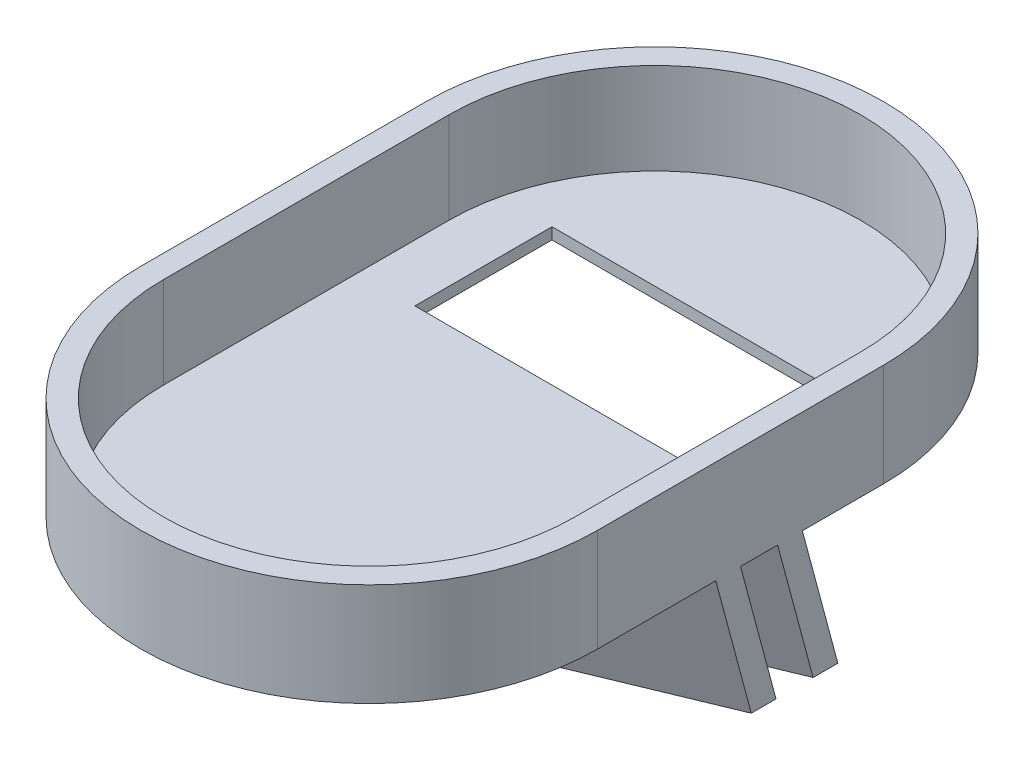
SolidWorks part; units mm, degrees
ref_plane "Front Plane" through (0, 0, 0) normal (0, 0, 1) x (1, 0, 0)
ref_plane "Top Plane" through (0, 0, 0) normal (0, 1, 0) x (1, 0, 0)
ref_plane "Right Plane" through (0, 0, 0) normal (1, 0, 0) x (0, 0, -1)
sketch "Sketch1" plane through (0, 0, 0) normal (0, 1, 0) x (1, 0, 0)
  line L0 (0, -12.5) -> (0, 12.5) construction
  line L1 (-18, -12.5) -> (-18, 12.5)
  line L2 (18, -12.5) -> (18, 12.5)
  line L4 (-13, 16.5) -> (13, 16.5)
  line L5 (-13, 16.5) -> (-13, 4.5)
  line L6 (-13, 4.5) -> (13, 4.5)
  line L7 (13, 16.5) -> (13, 4.5)
  line L8 (0, 4.5) -> (0, 16.5) construction
  line L9 (-13, 10.5) -> (13, 10.5) construction
  arc A0 (-18, -12.5) -> (18, -12.5) centre (0, -12.5) ccw
  arc A1 (18, 12.5) -> (-18, 12.5) centre (0, 12.5) ccw
  point P2 (0, 0)
  point P8 (0, 30.5)
  point P9 (0, -30.5)
  point P10 (0, 10.5)
  dimension "D2" = 61
  dimension "D1" = 36
  dimension "D3" = 12
  dimension "D4" = 26
  dimension "D5" = 14
extrude "Boss-Extrude1" add sketch "Sketch1" along normal blind 1
sketch "Sketch2" plane through (0, 0, 0) normal (0, 1, 0) x (1, 0, 0)
  line L2 (18, -12.5) -> (18, 12.5)
  line L3 (-18, 12.5) -> (-18, -12.5)
  line L4 (18, -12.5) -> (18, 12.5)
  line L5 (-18, 12.5) -> (-18, -12.5)
  line L8 (20, -12.5) -> (20, 12.5)
  line L9 (-20, 12.5) -> (-20, -12.5)
  line L10 (20, -12.5) -> (20, 12.5)
  line L11 (-20, 12.5) -> (-20, -12.5)
  arc A2 (-18, -12.5) -> (18, -12.5) centre (0, -12.5) ccw
  arc A3 (18, 12.5) -> (-18, 12.5) centre (0, 12.5) ccw
  arc A4 (-18, -12.5) -> (18, -12.5) centre (0, -12.5) ccw
  arc A5 (18, 12.5) -> (-18, 12.5) centre (0, 12.5) ccw
  arc A8 (-20, -12.5) -> (20, -12.5) centre (0, -12.5) ccw
  arc A9 (20, 12.5) -> (-20, 12.5) centre (0, 12.5) ccw
  arc A10 (-20, -12.5) -> (20, -12.5) centre (0, -12.5) ccw
  arc A11 (20, 12.5) -> (-20, 12.5) centre (0, 12.5) ccw
  dimension "D1" = 0
  dimension "D2" = 2
extrude "Boss-Extrude2" add sketch "Sketch2" along normal blind 9
sketch "Sketch3" plane through (0, 0, 0) normal (0, -1, 0) x (1, 0, 0)
  line L0 (-20, 0) -> (0, 8.2843)
  line L1 (-20, -12.5) -> (-20, 12.5) construction
  line L2 (0, 8.2843) -> (20, 0)
  line L3 (20, 12.5) -> (20, -12.5) construction
  line L6 (-20, -3.2472) -> (0, 5.0371)
  line L7 (0, 5.0371) -> (20, -3.2472)
  line L8 (-18.8519, -2.7716) -> (0, 5.0371) construction
  line L9 (0, 5.0371) -> (18.8519, -2.7716) construction
  line L10 (-20, 2.1648) -> (0, 10.4491)
  line L11 (0, 10.4491) -> (20, 2.1648)
  line L12 (-20, -5.412) -> (0, 2.8723)
  line L13 (0, 2.8723) -> (20, -5.412)
  line L14 (-20.7654, 1.8478) -> (0, 10.4491) construction
  line L15 (-19.2346, -5.0949) -> (0, 2.8723) construction
  line L16 (0, 10.4491) -> (20.7654, 1.8478) construction
  line L17 (0, 2.8723) -> (19.2346, -5.0949) construction
  line L18 (-20, 2.1648) -> (-20, 0)
  line L19 (-20, -3.2472) -> (-20, -5.412)
  line L20 (20, -5.412) -> (20, -3.2472)
  line L21 (20, 0) -> (20, 2.1648)
  dimension "D1" = 135
  dimension "D2" = 3
  dimension "D3" = 2
  dimension "D4" = 2
sketch "Sketch4" plane through (20, 0, 0) normal (1, 0, 0) x (0, 0, -1)
  line L0 (0, 0) -> (1.4599, -5.4483)
  line L1 (5.412, 0) -> (-2.8723, 0) construction
  dimension "D1" = 75
extrude "Boss-Extrude3" add sketch "Sketch3" along direction (0, -0.9659, -0.2588) on the side of the normal blind 12
fillet "Fillet1" radius 10 4 edges at (0, -5.7956, 1.3194) (0, -5.7956, 3.4842) (0, -5.7956, 6.7314) (0, -5.7956, 8.8961)
